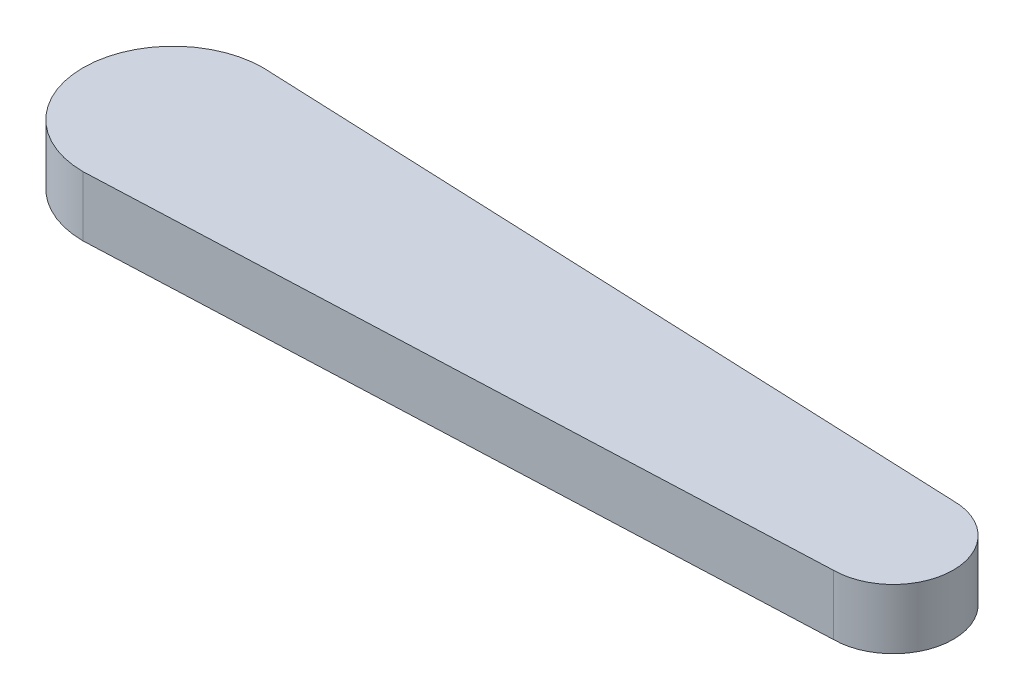
SolidWorks part; units mm, degrees
ref_plane "Front Plane" through (0, 0, 0) normal (0, 0, 1) x (1, 0, 0)
ref_plane "Top Plane" through (0, 0, 0) normal (0, 1, 0) x (1, 0, 0)
ref_plane "Right Plane" through (0, 0, 0) normal (1, 0, 0) x (0, 0, -1)
sketch "Sketch1" plane through (0, 0, 0) normal (0, 1, 0) x (1, 0, 0)
  line L0 (-5.5, 0) -> (5.5, 0) construction
  line L1 (-61.4666, 15) -> (58.5334, 10)
  line L2 (58.5334, 10) -> (58.5334, -10)
  line L3 (58.5334, -10) -> (-61.4666, -15)
  line L4 (-61.4666, -15) -> (-61.4666, 15)
  circle A0 centre (-61.4666, 0) radius 15
  circle A1 centre (58.5334, 0) radius 10
  dimension "D1" = 30
  dimension "D2" = 20
  dimension "D3" = 120
extrude "Boss-Extrude1" add sketch "Sketch1" along normal blind 10 contours A1 L1 A0 L3 | L4 A0 | L2 A1 | L3 A0 L1 L4 | L2 A1
